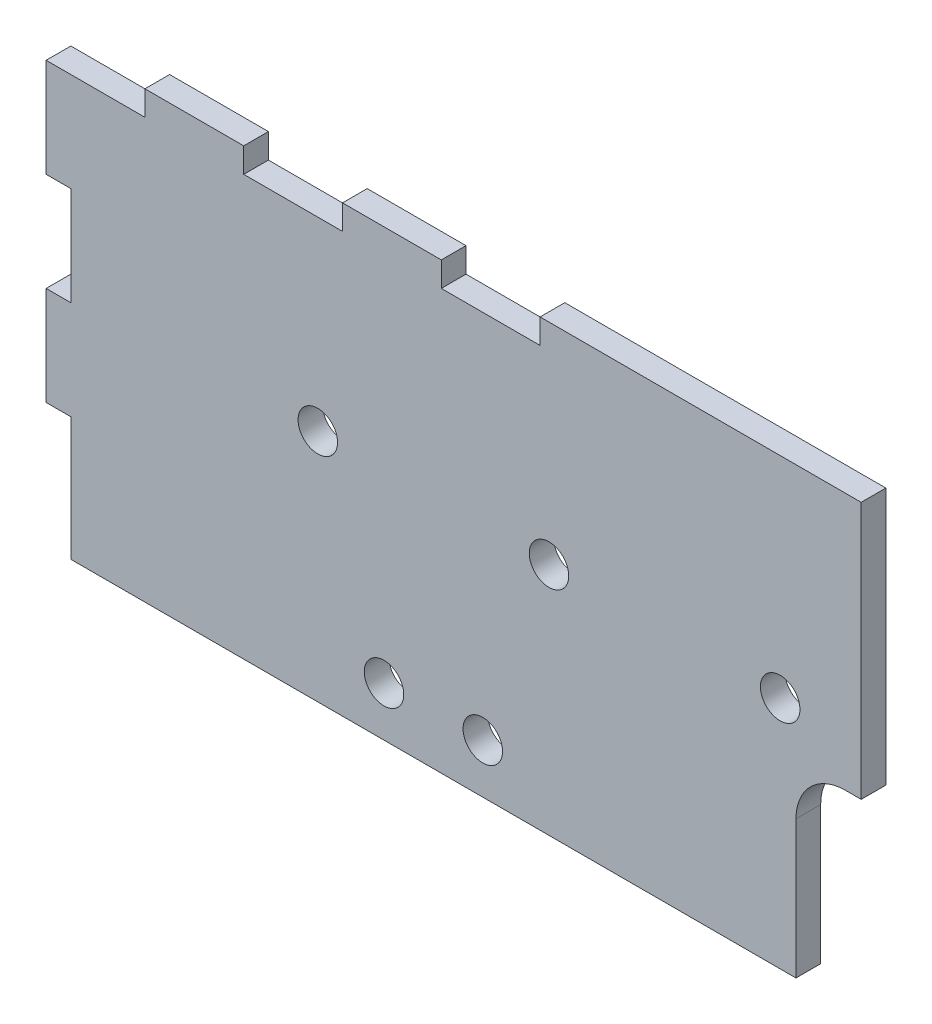
SolidWorks part; units mm, degrees
ref_plane "Front Plane" through (0, 0, 0) normal (0, 0, 1) x (1, 0, 0)
ref_plane "Top Plane" through (0, 0, 0) normal (0, 1, 0) x (1, 0, 0)
ref_plane "Right Plane" through (0, 0, 0) normal (1, 0, 0) x (0, 0, -1)
sketch "Sketch1" plane through (0, 0, 0) normal (0, 0, 1) x (1, 0, 0)
  line L0 (19.05, 6.35) -> (57.15, 6.35) construction
  line L1 (0, 0) -> (93.218, 0)
  line L2 (0, 0) -> (0, 57.15)
  line L4 (93.218, 0) -> (93.218, 24.0751)
  line L5 (0, 57.15) -> (44.45, 57.15)
  line L6 (0, 30.1498) -> (69.85, 30.1498) construction
  line L7 (31.75, 30.1498) -> (31.75, 32.6898) construction
  line L25 (69.85, 30.1498) -> (101.6, 30.1498) construction
  line L26 (46.609, 30.1498) -> (46.609, 0) construction
  line L27 (44.45, 57.15) -> (101.6, 57.15)
  line L29 (93.218, 24.0751) -> (101.6, 24.0751)
  line L30 (101.6, 57.15) -> (101.6, 24.0751)
  line L32 (0, 57.15) -> (9.525, 57.15)
  line L33 (0, 57.15) -> (0, 53.975)
  line L34 (0, 53.975) -> (9.525, 53.975)
  line L35 (9.525, 57.15) -> (9.525, 53.975)
  line L36 (9.525, 53.975) -> (22.225, 53.975)
  line L37 (9.525, 53.975) -> (9.525, 57.15)
  line L38 (9.525, 57.15) -> (22.225, 57.15)
  line L39 (22.225, 53.975) -> (22.225, 57.15)
  line L40 (22.225, 53.975) -> (34.925, 53.975)
  line L41 (22.225, 53.975) -> (22.225, 57.15)
  line L42 (22.225, 57.15) -> (34.925, 57.15)
  line L43 (34.925, 53.975) -> (34.925, 57.15)
  line L45 (34.925, 53.975) -> (34.925, 57.15)
  line L46 (34.925, 57.15) -> (44.45, 57.15)
  line L50 (44.45, 57.15) -> (50.8, 57.15)
  line L52 (34.925, 53.975) -> (47.625, 53.975)
  line L53 (34.925, 53.975) -> (34.925, 57.15)
  line L54 (34.925, 57.15) -> (47.625, 57.15)
  line L55 (47.625, 53.975) -> (47.625, 57.15)
  line L56 (47.625, 53.975) -> (60.325, 53.975)
  line L57 (47.625, 53.975) -> (47.625, 57.15)
  line L58 (47.625, 57.15) -> (60.325, 57.15)
  line L59 (60.325, 53.975) -> (60.325, 57.15)
  line L60 (60.325, 53.975) -> (73.025, 53.975)
  line L61 (60.325, 53.975) -> (60.325, 57.15)
  line L62 (60.325, 57.15) -> (73.025, 57.15)
  line L63 (73.025, 53.975) -> (73.025, 57.15)
  line L64 (0, 53.975) -> (-3.175, 53.975)
  line L65 (0, 53.975) -> (0, 41.275)
  line L66 (0, 41.275) -> (-3.175, 41.275)
  line L67 (-3.175, 53.975) -> (-3.175, 41.275)
  line L68 (0, 28.575) -> (-3.175, 28.575)
  line L69 (0, 28.575) -> (0, 15.875)
  line L70 (0, 15.875) -> (-3.175, 15.875)
  line L71 (-3.175, 28.575) -> (-3.175, 15.875)
  circle A0 centre (40.259, 6.35) radius 2.54
  circle A1 centre (52.959, 6.35) radius 2.54
  circle A2 centre (31.75, 30.1498) radius 2.54
  circle A3 centre (61.468, 30.1498) radius 2.54
  circle A5 centre (91.186, 30.1498) radius 2.54
  point P1 (50.8, 88.9)
  dimension "D3" = 5.08
  dimension "D4" = 5.08
  dimension "D8" = 5.08
  dimension "D9" = 5.08
  dimension "D6" = 5.08
  dimension "D5" = 12.7
  dimension "D7" = 6.35
  dimension "D10" = 29.718
  dimension "D13" = 30.1498
  dimension "D2" = 101.6
  dimension "D11" = 29.718
  dimension "D12" = 3.175
  dimension "D14" = 9.525
  dimension "D16" = 57.15
  dimension "D17" = 12.7
  dimension "D15" = 12.7
  dimension "D18" = 12.7
  dimension "D19" = 12.7
  dimension "D20" = 12.7
  dimension "D21" = 3.175
  dimension "D22" = 12.7
  dimension "D23" = 3.175
  dimension "D24" = 12.7
  dimension "D25" = 12.7
  dimension "D26" = 31.75
  dimension "D27" = 14.859
  dimension "D28" = 6.35
  dimension "D29" = 6.35
extrude "Boss-Extrude1" add sketch "Sketch1" along normal blind 3.175
fillet "Fillet1" radius 6.35 1 edges at (93.218, 24.0751, 1.5875)
equation "\"hole-size\"=0.2"
equation "\"D8@Sketch1\"=\"hole-size\""
equation "\"D9@Sketch1\"=\"hole-size\""
equation "\"D4@Sketch1\"=\"hole-size\""
equation "\"D3@Sketch1\"=\"hole-size\""
